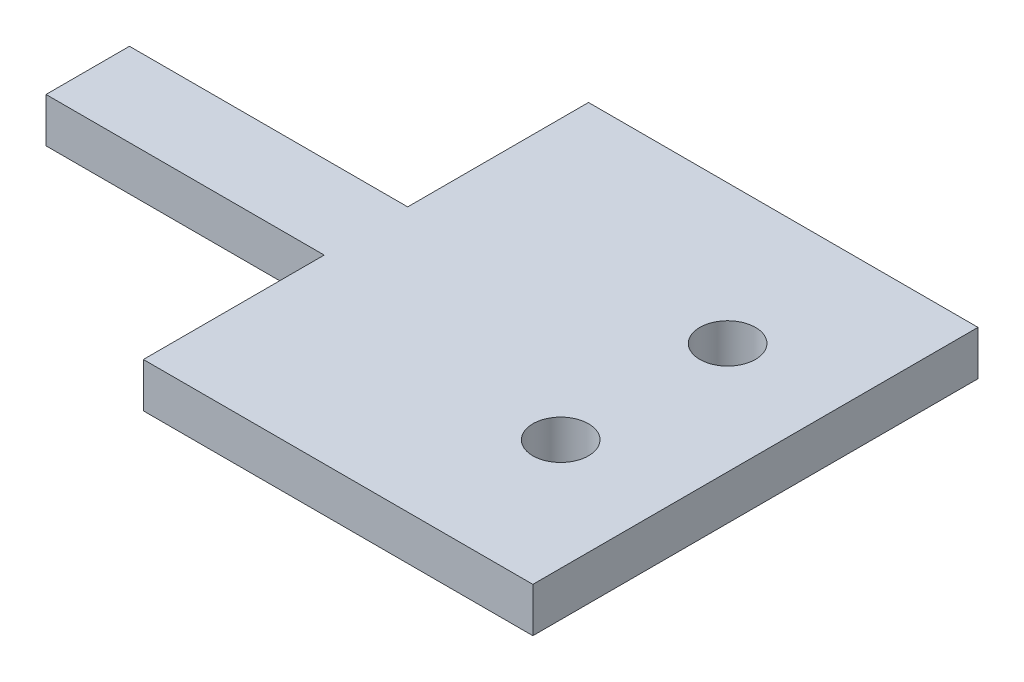
SolidWorks part; units mm, degrees
ref_plane "前视基准面" through (0, 0, 0) normal (0, 0, 1) x (1, 0, 0)
ref_plane "上视基准面" through (0, 0, 0) normal (0, 1, 0) x (1, 0, 0)
ref_plane "右视基准面" through (0, 0, 0) normal (1, 0, 0) x (0, 0, -1)
sketch "Sketch1" plane through (0, 0, 0) normal (0, 1, 0) x (1, 0, 0)
  line L0 (-60, 0) -> (-10, 0) construction
  line L1 (-60, -40) -> (60, -40) construction
  line L2 (-60, -40) -> (-60, 40) construction
  line L3 (-60, 40) -> (60, 40) construction
  line L4 (60, -40) -> (60, 40)
  line L5 (-60, -40) -> (60, 40) construction
  line L6 (-60, 40) -> (60, -40) construction
  line L7 (-10, 40) -> (-10, -40) construction
  line L8 (-60, 7.5) -> (-10, 7.5)
  line L9 (-60, -7.5) -> (-10, -7.5)
  line L10 (-60, 7.5) -> (-60, -7.5)
  line L11 (-10, 0) -> (60, 0) construction
  line L12 (40, 15) -> (40, -15) construction
  line L13 (-10, 7.5) -> (-10, 40)
  line L14 (-10, 40) -> (60, 40)
  line L20 (60, -40) -> (-10, -40)
  line L21 (-10, -40) -> (-10, -7.5)
  circle A0 centre (40, 15) radius 5
  circle A1 centre (40, -15) radius 5
  point P0 (0, 0)
  point P17 (40, 0)
  dimension "D6" = 10
  dimension "D1" = 50
  dimension "D2" = 80
  dimension "D3" = 15
  dimension "D4" = 70
  dimension "D5" = 20
  dimension "D7" = 30
extrude "Boss-Extrude1" add sketch "Sketch1" along normal blind 8
